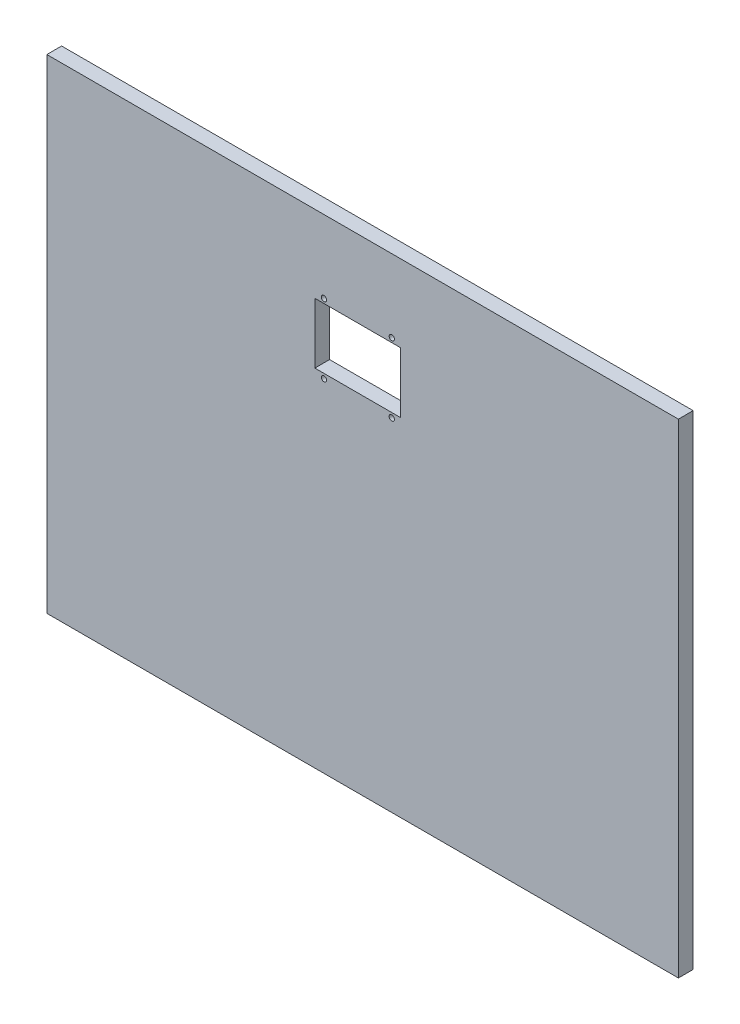
SolidWorks part; units mm, degrees
ref_plane "Front Plane" through (0, 0, 0) normal (0, 0, 1) x (1, 0, 0)
ref_plane "Top Plane" through (0, 0, 0) normal (0, 1, 0) x (1, 0, 0)
ref_plane "Right Plane" through (0, 0, 0) normal (1, 0, 0) x (0, 0, -1)
sketch "Sketch1" plane through (0, 0, 0) normal (0, 0, 1) x (1, 0, 0)
  line L1 (0, 0) -> (214, 0)
  line L2 (0, 0) -> (0, 164)
  line L3 (0, 164) -> (214, 164)
  line L4 (214, 0) -> (214, 164)
  line L9 (119.81, 137.8832) -> (90.81, 137.8832)
  line L10 (119.81, 137.8832) -> (119.81, 117.3832)
  line L11 (119.81, 117.3832) -> (90.81, 117.3832)
  line L12 (90.81, 137.8832) -> (90.81, 117.3832)
  circle A0 centre (93.9009, 139.3479) radius 0.9
  circle A1 centre (116.882, 139.3479) radius 0.9
  circle A2 centre (116.8574, 115.7916) radius 0.9
  circle A3 centre (93.9009, 115.7916) radius 0.9
  dimension "D3" = 1.8
  dimension "D1" = 214
  dimension "D2" = 164
  dimension "D4" = 29
  dimension "D5" = 20.5
extrude "Boss-Extrude1" add sketch "Sketch1" along normal blind 5
